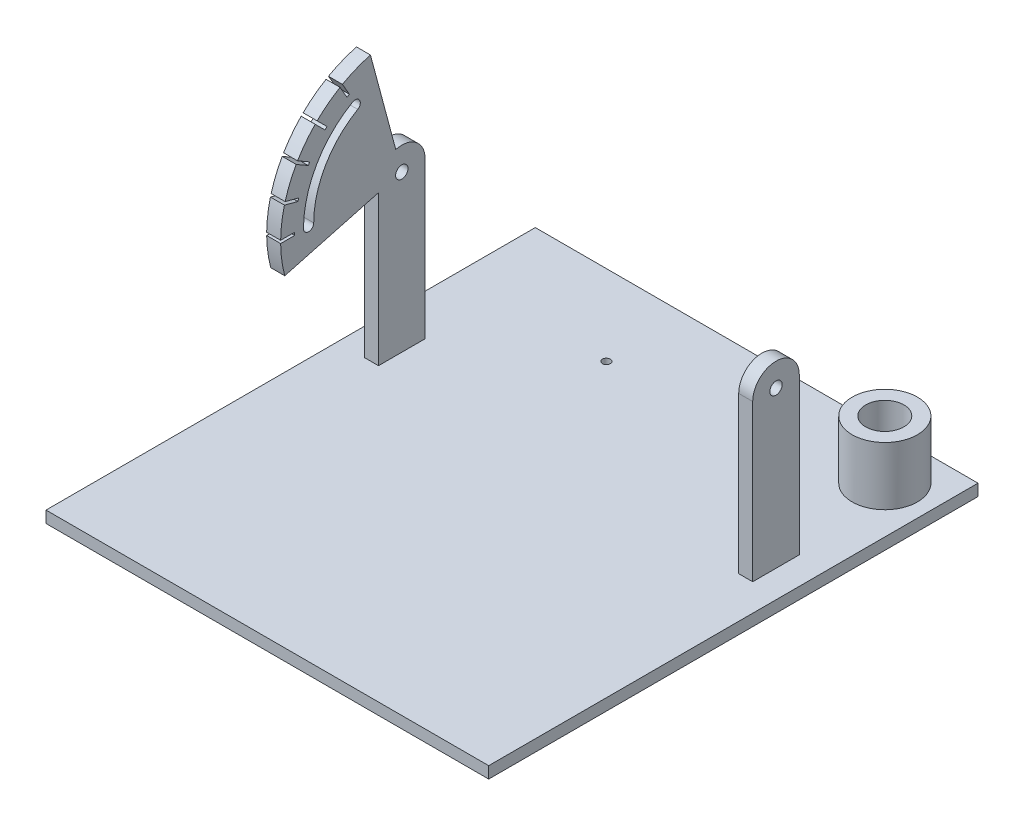
SolidWorks part; units mm, degrees
ref_plane "Front Plane" through (0, 0, 0) normal (0, 0, 1) x (1, 0, 0)
ref_plane "Top Plane" through (0, 0, 0) normal (0, 1, 0) x (1, 0, 0)
ref_plane "Right Plane" through (0, 0, 0) normal (1, 0, 0) x (0, 0, -1)
sketch "Croquis_base" plane through (0, 0, 0) normal (0, 1, 0) x (1, 0, 0)
  line L1 (-95, -135) -> (95, -135)
  line L2 (-95, -135) -> (-95, 75)
  line L3 (-95, 75) -> (95, 75)
  line L4 (95, -135) -> (95, 75)
  line L5 (-95, -135) -> (95, 75) construction
  line L6 (-95, 75) -> (95, -135) construction
  point P0 (0, -30)
  dimension "D1" = 190
  dimension "D2" = 210
extrude "Placa_base" add sketch "Croquis_base" along normal blind 5
sketch "Croquis_tornillos_caja" plane through (0, 0, 0) normal (0, 1, 0) x (1, 0, 0)
  circle A0 centre (-30, 40.5) radius 1.7
  circle A1 centre (30, 40.5) radius 1.7
  dimension "D1" = 3.4
extrude "Agujeros_caja" cut sketch "Croquis_tornillos_caja" along normal through all and the other way through all
ref_plane "Plano_Top Plane_+5" through (0, 5, 0) normal (0, 1, 0) x (1, 0, 0)
sketch "Croquis_zocalo" plane through (0, 5, 0) normal (0, 1, 0) x (1, 0, 0)
  circle A0 centre (75, 55) radius 14
  dimension "D1" = 28
extrude "Zocalo_mastil" add sketch "Croquis_zocalo" along normal blind 25
ref_plane "Plano_Top Plane_+30" through (0, 30, 0) normal (0, 1, 0) x (1, 0, 0)
sketch "Croquis_zocalo_hueco" plane through (0, 30, 0) normal (0, 1, 0) x (1, 0, 0)
  circle A0 centre (75, 55) radius 8.2
  dimension "D1" = 16.4
extrude "Zocalo_hueco" cut sketch "Croquis_zocalo_hueco" against normal blind 22
ref_plane "Plano_Right Plane_+77_3" through (77.3, 0, 0) normal (1, 0, 0) x (0, 0, -1)
sketch "Croquis_torre_der" plane through (77.3, 0, 0) normal (1, 0, 0) x (0, 0, -1)
  line L0 (-10, 0) -> (10, 0)
  line L1 (10, 0) -> (10, 72)
  line L2 (-10, 72) -> (-10, 0)
  arc A0 (10, 72) -> (-10, 72) centre (0, 72) ccw
extrude "Torre_derecha" add sketch "Croquis_torre_der" along normal blind 6
ref_plane "Plano_Right Plane_-77_3" through (-77.3, 0, 0) normal (1, 0, 0) x (0, 0, -1)
sketch "Croquis_torre_izq" plane through (-77.3, 0, 0) normal (1, 0, 0) x (0, 0, -1)
  line L0 (-10, 0) -> (10, 0)
  line L1 (10, 0) -> (10, 72)
  line L2 (-10, 72) -> (-10, 0)
  arc A0 (10, 72) -> (-10, 72) centre (0, 72) ccw
extrude "Torre_izquierda" add sketch "Croquis_torre_izq" against normal blind 6
sketch "Croquis_abanico" plane through (-77.3, 0, 0) normal (1, 0, 0) x (0, 0, -1)
  line L0 (0, 72) -> (-13.4586, 122.2281)
  line L1 (-50.2281, 58.5414) -> (0, 72)
  arc A0 (-13.4586, 122.2281) -> (-50.2281, 58.5414) centre (0, 72) ccw
extrude "Abanico" add sketch "Croquis_abanico" against normal blind 6
sketch "Croquis_ranura_arco" plane through (0, 0, 0) normal (1, 0, 0) x (0, 0, -1)
  arc A0 (-21.1, 108.5463) -> (-42.2, 72) centre (0, 72) ccw
  arc A1 (-18.9, 104.7358) -> (-37.8, 72) centre (0, 72) ccw
  arc A2 (-42.2, 72) -> (-37.8, 72) centre (-40, 72) ccw
  arc A3 (-18.9, 104.7358) -> (-21.1, 108.5463) centre (-20, 106.641) ccw
extrude "Ranura_arco" cut sketch "Croquis_ranura_arco" along normal through all and the other way through all
sketch "Croquis_marcas_15" plane through (0, 0, 0) normal (1, 0, 0) x (0, 0, -1)
  line L0 (-46, 71.4) -> (-52.5, 71.4)
  line L1 (-52.5, 71.4) -> (-52.5, 72.6)
  line L2 (-52.5, 72.6) -> (-46, 72.6)
  line L3 (-46, 72.6) -> (-46, 71.4)
  line L4 (-44.5879, 83.3261) -> (-50.8664, 85.0084)
  line L5 (-50.8664, 85.0084) -> (-50.5558, 86.1676)
  line L6 (-50.5558, 86.1676) -> (-44.2773, 84.4852)
  line L7 (-44.2773, 84.4852) -> (-44.5879, 83.3261)
  line L8 (-40.1372, 94.4804) -> (-45.7663, 97.7304)
  line L9 (-45.7663, 97.7304) -> (-45.1663, 98.7696)
  line L10 (-45.1663, 98.7696) -> (-39.5372, 95.5196)
  line L11 (-39.5372, 95.5196) -> (-40.1372, 94.4804)
  line L12 (-32.9512, 104.1026) -> (-37.5474, 108.6988)
  line L13 (-37.5474, 108.6988) -> (-36.6988, 109.5474)
  line L14 (-36.6988, 109.5474) -> (-32.1026, 104.9512)
  line L15 (-32.1026, 104.9512) -> (-32.9512, 104.1026)
  line L16 (-23.5196, 111.5372) -> (-26.7696, 117.1663)
  line L17 (-26.7696, 117.1663) -> (-25.7304, 117.7663)
  line L18 (-25.7304, 117.7663) -> (-22.4804, 112.1372)
  line L19 (-22.4804, 112.1372) -> (-23.5196, 111.5372)
extrude "Marcas_angulo" cut sketch "Croquis_marcas_15" along normal through all and the other way through all
sketch "Croquis_pivote" plane through (0, 0, 0) normal (1, 0, 0) x (0, 0, -1)
  circle A0 centre (0, 72) radius 2.65
  dimension "D1" = 5.3
extrude "Agujero_pivote_M5" cut sketch "Croquis_pivote" along normal through all and the other way through all
